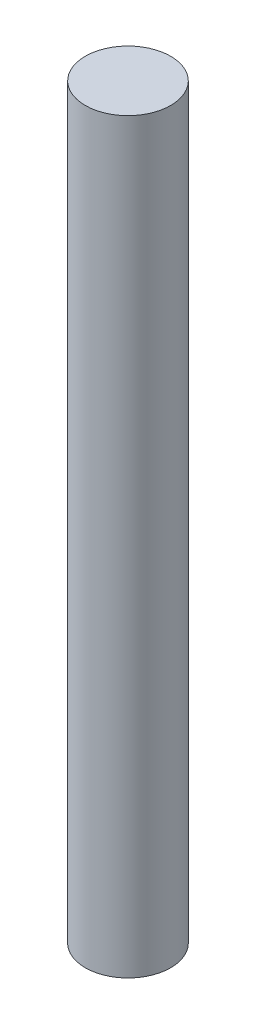
SolidWorks part; units mm, degrees
ref_plane "前视基准面" through (0, 0, 0) normal (0, 0, 1) x (1, 0, 0)
ref_plane "上视基准面" through (0, 0, 0) normal (0, 1, 0) x (1, 0, 0)
ref_plane "右视基准面" through (0, 0, 0) normal (1, 0, 0) x (0, 0, -1)
sketch "草图1" plane through (0, 0, 0) normal (0, 1, 0) x (1, 0, 0)
  circle A0 centre (0, 0) radius 4
  dimension "D1" = 8
extrude "凸台-拉伸1" add sketch "草图1" along normal blind 70
